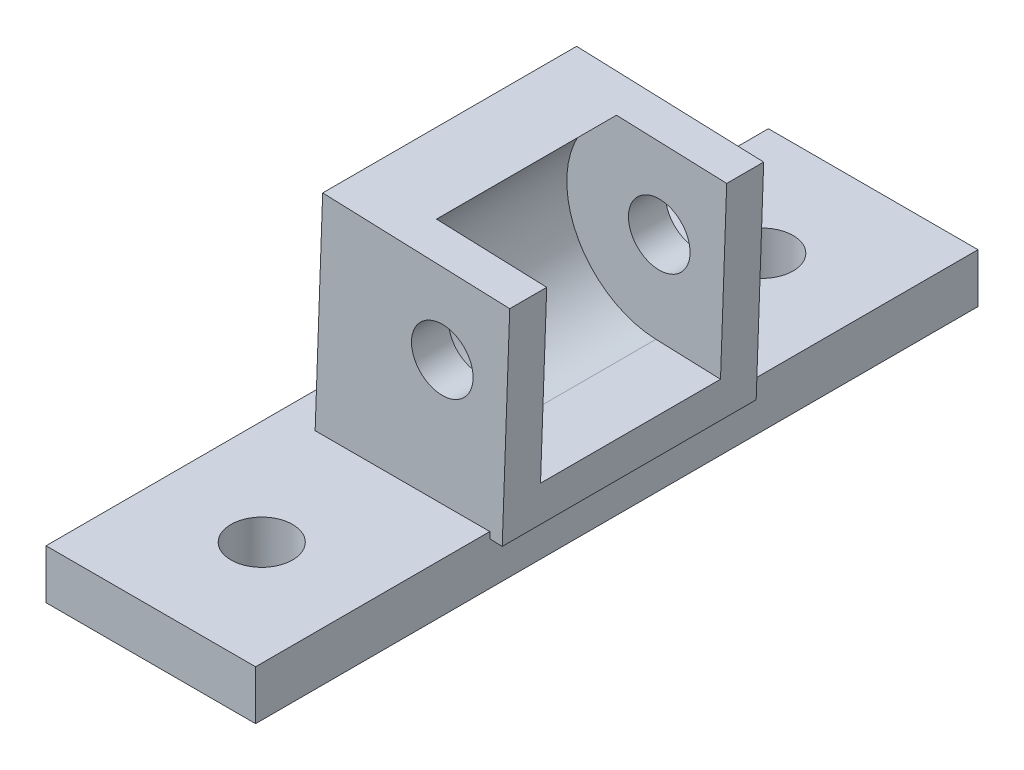
SolidWorks part; units mm, degrees
ref_plane "Front Plane" through (0, 0, 0) normal (0, 0, 1) x (1, 0, 0)
ref_plane "Top Plane" through (0, 0, 0) normal (0, 1, 0) x (1, 0, 0)
ref_plane "Right Plane" through (0, 0, 0) normal (1, 0, 0) x (0, 0, -1)
sketch "Sketch1" plane through (0, 0, 0) normal (0, 0, 1) x (1, 0, 0)
  line L0 (-339.1971, 118.0363) -> (-358.468, 118.7282)
  line L1 (-358.468, 118.7282) -> (-359.2436, 97.1267)
  line L2 (-359.2436, 97.1267) -> (-339.9726, 96.4348)
  line L3 (-339.9726, 96.4348) -> (-339.1971, 118.0363)
  line L4 (-330.9022, 102.2853) -> (-352.6762, 103.0671) construction
  line L5 (-330.7578, 99.9164) -> (-346.4865, 100.4811) construction
  line L6 (-330.7578, 99.9164) -> (-346.4865, 100.4811)
  arc A0 (-352.6762, 103.0671) -> (-346.4865, 100.4811) centre (-346.1447, 110) ccw construction
  arc A1 (-352.1622, 117.3835) -> (-352.6762, 103.0671) centre (-346.1447, 110) ccw construction
  arc A2 (-345.8029, 119.5189) -> (-352.1622, 117.3835) centre (-346.1447, 110) ccw construction
  arc A3 (-352.6762, 103.0671) -> (-346.4865, 100.4811) centre (-346.1447, 110) ccw
  arc A4 (-352.1622, 117.3835) -> (-352.6762, 103.0671) centre (-346.1447, 110) ccw
  arc A5 (-345.8029, 119.5189) -> (-352.1622, 117.3835) centre (-346.1447, 110) ccw
  dimension "D1" = 6.35
  dimension "D2" = 3.81
extrude "Boss-Extrude1" add sketch "Sketch1" against normal blind 22.352 contours A5 L0 L1 L2 L3 L6 A3 A4
sketch "Sketch2" plane through (0, 0, -22.352) normal (0, 0, -1) x (-1, 0, 0)
  line L0 (358.468, 118.7282) -> (359.2436, 97.1267)
  line L1 (359.2436, 97.1267) -> (339.9726, 96.4348)
  line L2 (339.9726, 96.4348) -> (339.1971, 118.0363)
  line L3 (339.1971, 118.0363) -> (358.468, 118.7282)
  circle A0 centre (346.1447, 110) radius 3.175 construction
  circle A1 centre (346.1447, 110) radius 3.175
  circle A2 centre (346.1447, 110) radius 3.175
  arc M6 (350.552, 118.444) -> (346.4865, 100.4811) centre (346.1447, 110) cw
  line M7 (346.4865, 100.4811) -> (339.8359, 100.2424)
extrude "Boss-Extrude3" add sketch "Sketch2" against normal blind 3.81 contours L3 L2 A1 M7 M6
sketch "Sketch3" plane through (0, 0, 0) normal (0, 0, 1) x (1, 0, 0)
  line L0 (-358.468, 118.7282) -> (-359.2436, 97.1267)
  line L1 (-359.2436, 97.1267) -> (-339.9726, 96.4348)
  line L2 (-339.9726, 96.4348) -> (-339.1971, 118.0363)
  line L3 (-339.1971, 118.0363) -> (-358.468, 118.7282)
extrude "Boss-Extrude4" add sketch "Sketch3" along normal blind 3.81
sketch "Sketch6" plane through (0, 0, 0) normal (0, 0, -1) x (-1, 0, 0)
  circle A0 centre (346.1447, 110) radius 3.175
extrude "Cut-Extrude1" cut sketch "Sketch6" against normal blind 3.81
ref_plane "Plane1" through (0, 97.1267, 0) normal (0, 1, 0) x (1, 0, 0)
sketch "Sketch7" plane through (0, 97.1267, 0) normal (0, 1, 0) x (1, 0, 0)
  line L1 (-362.8396, 46.482) -> (-341.2496, 46.482)
  line L2 (-362.8396, 46.482) -> (-362.8396, -27.94)
  line L3 (-362.8396, -27.94) -> (-341.2496, -27.94)
  line L4 (-341.2496, 46.482) -> (-341.2496, -27.94)
  circle A0 centre (-352.0446, 35.052) radius 3.175
  circle A1 centre (-352.0446, -16.51) radius 3.175
  dimension "D5" = 10.795
  dimension "D7" = 6.35
  dimension "D8" = 6.35
  dimension "D1" = 24.13
  dimension "D2" = 24.13
  dimension "D3" = 21.59
  dimension "D4" = 10.795
  dimension "D6" = 11.43
  dimension "D9" = 11.43
extrude "Boss-Extrude6" add sketch "Sketch7" against normal blind 5.08 contours L2 L1 L4 L3
sketch "Sketch9" plane through (0, 97.1267, 0) normal (0, 1, 0) x (1, 0, 0)
  line L0 (-362.8396, 46.482) -> (-362.8396, -27.94) construction
  line L1 (-362.8396, -27.94) -> (-341.2496, -27.94) construction
  line L2 (-362.8396, 46.482) -> (-341.2496, 46.482) construction
  circle A0 centre (-352.0446, -16.51) radius 3.175
  circle A1 centre (-352.0446, 35.052) radius 3.175
  dimension "D1" = 6.35
  dimension "D4" = 10.795
  dimension "D5" = 6.35
  dimension "D2" = 10.795
  dimension "D3" = 11.43
  dimension "D6" = 11.43
extrude "Cut-Extrude2" cut sketch "Sketch9" against normal blind 6.35
